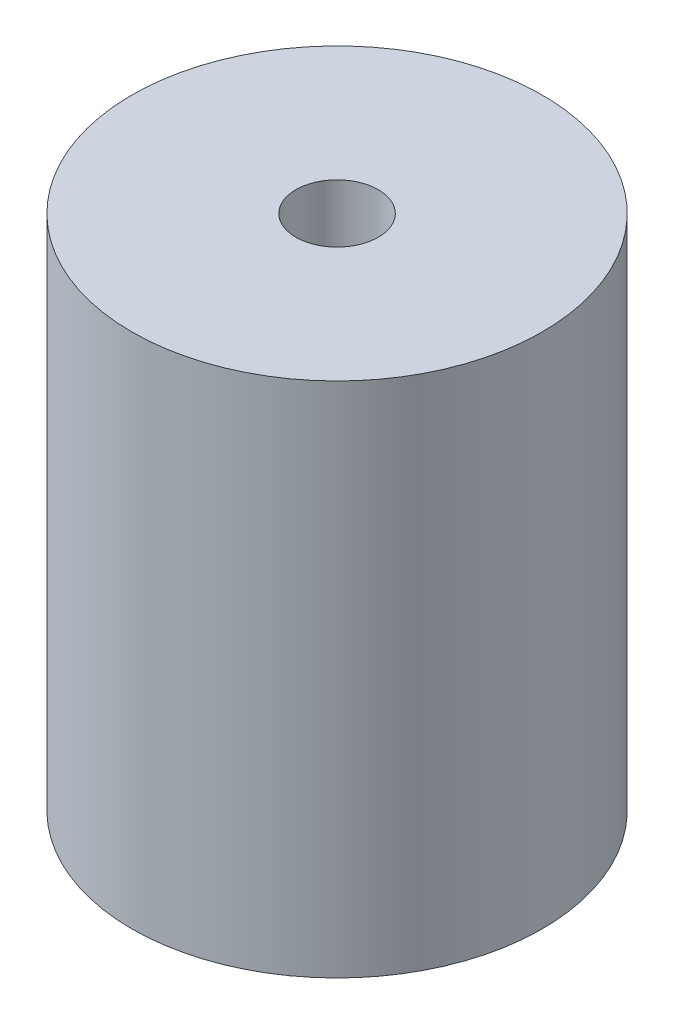
SolidWorks part; units mm, degrees
material "Delrin 2700 NC010, Low Viscosity Acetal Copolymer (SS)"
ref_plane "Front Plane" through (0, 0, 0) normal (0, 0, 1) x (1, 0, 0)
ref_plane "Top Plane" through (0, 0, 0) normal (0, 1, 0) x (1, 0, 0)
ref_plane "Right Plane" through (0, 0, 0) normal (1, 0, 0) x (0, 0, -1)
sketch "Sketch1" plane through (0, 0, 0) normal (0, 1, 0) x (1, 0, 0)
  circle A0 centre (0, 0) radius 12.7
  dimension "D1" = 25.4
extrude "Boss-Extrude1" add sketch "Sketch1" along normal blind 32
sketch "Sketch2" plane through (0, 0, 0) normal (0, -1, 0) x (1, 0, 0)
  point P0 (0, 0)
hole_wizard "Tap Drill for 1/4-20 Tap1" positions "Sketch2" profile "Sketch3" hole size "1/4-20" standard "ANSI Inch"
sketch "Sketch3" plane through (0, 0, 0) normal (1, 0, 0) x (0, 0, -1)
  line L0 (0, 0) -> (0, 9.1538)
  line L1 (0, 9.1538) -> (2.5527, 7.62)
  line L2 (2.5527, 7.62) -> (2.5527, 0)
  line L5 (2.5527, 0) -> (0, 0)
  line L10 (0, 9.1538) -> (-2.5527, 7.62) construction
  line L11 (0, -6.35) -> (0, 107.95) construction
  dimension "Hole Dia." = 5.1054
  dimension "Hole Depth" = 7.62
  dimension "Drill Angle" = 118
sketch "Sketch4" plane through (0, 32, 0) normal (0, 1, 0) x (1, 0, 0)
  point P0 (0, 0)
hole_wizard "Tap Drill for 1/4-20 Tap2" positions "Sketch4" profile "Sketch5" hole size "1/4-20" standard "ANSI Inch"
sketch "Sketch5" plane through (0, 32, 0) normal (1, 0, 0) x (0, 0, 1)
  line L0 (0, 0) -> (0, 9.1538)
  line L1 (0, 9.1538) -> (2.5527, 7.62)
  line L2 (2.5527, 7.62) -> (2.5527, 0)
  line L5 (2.5527, 0) -> (0, 0)
  line L10 (0, 9.1538) -> (-2.5527, 7.62) construction
  line L11 (0, -6.35) -> (0, 107.95) construction
  dimension "Hole Dia." = 5.1054
  dimension "Hole Depth" = 7.62
  dimension "Drill Angle" = 118
